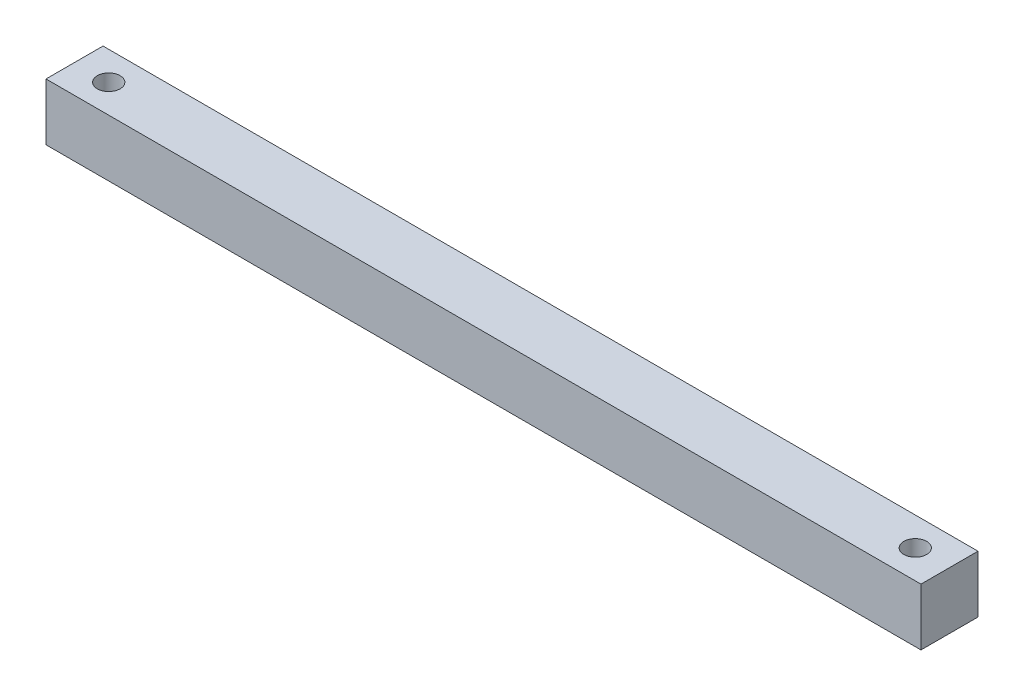
SolidWorks part; units mm, degrees
ref_plane "Front Plane" through (0, 0, 0) normal (0, 0, 1) x (1, 0, 0)
ref_plane "Top Plane" through (0, 0, 0) normal (0, 1, 0) x (1, 0, 0)
ref_plane "Right Plane" through (0, 0, 0) normal (1, 0, 0) x (0, 0, -1)
sketch "Sketch2" plane through (0, 0, 0) normal (0, 0, 1) x (1, 0, 0)
  line L1 (-38.3553, 2.5) -> (38.3553, 2.5)
  line L2 (-38.3553, 2.5) -> (-38.3553, -2.5)
  line L3 (-38.3553, -2.5) -> (38.3553, -2.5)
  line L4 (38.3553, 2.5) -> (38.3553, -2.5)
  line L5 (-38.3553, 2.5) -> (38.3553, -2.5) construction
  line L6 (-38.3553, -2.5) -> (38.3553, 2.5) construction
  point P0 (0, 0)
  dimension "D1" = 5
  dimension "D2" = 76.7107
extrude "Boss-Extrude1" add sketch "Sketch2" along normal blind 5
sketch "Sketch3" plane through (0, 2.5, 0) normal (0, 1, 0) x (1, 0, 0)
  line L0 (-38.3553, -2.5) -> (38.3553, -2.5) construction
  line L1 (-38.3553, -5) -> (-38.3553, 0) construction
  line L2 (38.3553, -5) -> (38.3553, 0) construction
  circle A0 centre (-35.3553, -2.5) radius 1
  circle A1 centre (35.3553, -2.5) radius 1
  dimension "D2" = 2
  dimension "D4" = 2
  dimension "D1" = 3
  dimension "D3" = 3
extrude "Cut-Extrude1" cut sketch "Sketch3" against normal through all
